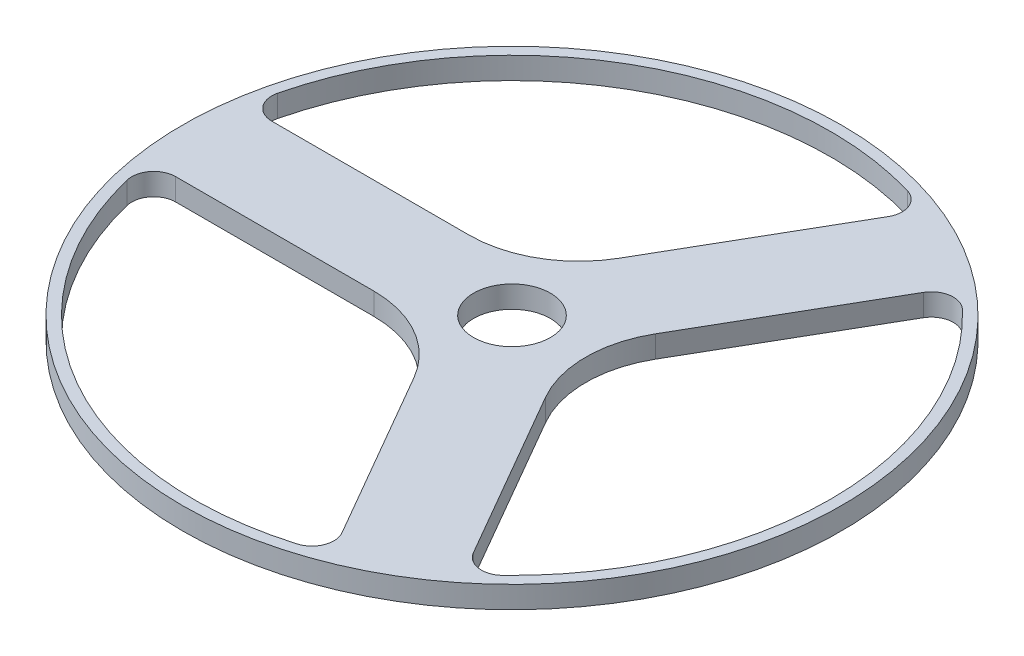
SolidWorks part; units mm, degrees
ref_plane "Front Plane" through (0, 0, 0) normal (0, 0, 1) x (1, 0, 0)
ref_plane "Top Plane" through (0, 0, 0) normal (0, 1, 0) x (1, 0, 0)
ref_plane "Right Plane" through (0, 0, 0) normal (1, 0, 0) x (0, 0, -1)
sketch "Sketch1" plane through (0, 0, 0) normal (0, 1, 0) x (1, 0, 0)
  line L0 (0, 15) -> (0, 0) construction
  line L1 (0, 0) -> (-12.9904, -7.5) construction
  line L2 (0, 0) -> (12.9904, -7.5) construction
  circle A0 centre (0, 0) radius 46.5
  circle A1 centre (0, 15) radius 6.5
  circle A2 centre (-12.9904, -7.5) radius 10
  circle A3 centre (12.9904, -7.5) radius 3.5
  circle A4 centre (0, 0) radius 3.5
  point P3 (0, 15)
  point P8 (12.9904, -7.5)
  point P9 (-12.9904, -7.5)
  point P10 (0, 0)
  dimension "D1" = 93
  dimension "D4" = 13
  dimension "D5" = 20
  dimension "D6" = 7
  dimension "D7" = 7
  dimension "D2" = 15
  dimension "D3" = 3
extrude "Boss-Extrude1" add sketch "Sketch1" along normal blind 2
sketch "Sketch2" plane through (0, 2, 0) normal (0, 1, 0) x (1, 0, 0)
  line L0 (0, 0) -> (12.9904, -7.5) construction
  line L1 (0, 0) -> (0, 46.5) construction
  line L2 (0, 0) -> (-12.9904, -7.5) construction
  line L3 (0, 0) -> (-40.2702, -23.25) construction
  line L4 (0, 0) -> (40.2702, -23.25) construction
  circle A0 centre (0, 0) radius 46.5 construction
  circle A1 centre (-12.9904, -7.5) radius 10 construction
  circle A2 centre (12.9904, -7.5) radius 3.5 construction
  circle A3 centre (0, 0) radius 25
  circle A4 centre (21.6506, -12.5) radius 3
  circle A5 centre (-21.6506, -12.5) radius 3
  circle A6 centre (0, 25) radius 3
  point P22 (0, 0)
  dimension "D1" = 50
  dimension "D2" = 6
  dimension "D3" = 3
ref_plane "Plane1" through (0, 0, 0) normal (-0.5, 0, -0.866) x (-0.866, 0, 0.5)
sketch "Sketch3" plane through (0, 2, 0) normal (0, 1, 0) x (1, 0, 0)
  circle A0 centre (0, 0) radius 3.5
  circle A1 centre (0, 0) radius 5
  dimension "D1" = 10
extrude "Boss-Extrude2" add sketch "Sketch3" along normal blind 100
sketch "Sketch4" plane through (0, 102, 0) normal (0, 1, 0) x (1, 0, 0)
  line L0 (-29, 0) -> (-5.1, 0) construction
  line L6 (0, 0) -> (-1.7447, 3.0342) construction
  line L11 (-8.2882, 4.3733) -> (-28.6683, 4.3733)
  line L16 (-8.2093, -4.3733) -> (-28.6683, -4.3733)
  line L17 (7.9863, 5.0683) -> (18.1286, 22.6353)
  line L18 (0.372, 9.3733) -> (10.5551, 27.0109)
  line L19 (0.4509, -9.3733) -> (10.6194, -26.9857)
  line L20 (7.9863, -4.9317) -> (18.1825, -22.592)
  line L21 (0, 0) -> (-3.028, 1.7553)
  line L22 (0, 0) -> (0.0061, 3.5)
  line L23 (0, 0) -> (3.0342, 1.7447)
  line L24 (0, 0) -> (3.028, -1.7553)
  line L25 (0, 0) -> (-0.0061, -3.5)
  line L26 (0, 0) -> (-3.0342, -1.7447)
  line L27 (0, 0) -> (0, 3.5) construction
  line L28 (-3.5, 0) -> (0, 0) construction
  line L29 (0, 29) -> (0, 54.3686) construction
  circle A0 centre (0, 0) radius 30
  circle A1 centre (0, 0) radius 29
  circle A3 centre (0, 0) radius 3.5
  arc A4 (-8.2093, -4.3733) -> (0.4509, -9.3733) centre (-8.2093, -14.3733) cw
  arc A6 (7.9863, -4.9317) -> (7.9863, 5.0683) centre (16.6465, 0.0683) cw
  arc A7 (-8.2882, 4.3733) -> (0.372, 9.3733) centre (-8.2882, 14.3733) ccw
  point P17 (0, 0)
  point P21 (0.0497, 0.0228)
  point P23 (0, 0)
  point P32 (0, 0)
  point P33 (5.0995, 0.0683)
  dimension "D1" = 60
  dimension "D2" = 58
  dimension "D12" = 10
  dimension "D4" = 3
  dimension "D7" = 8.7466
  dimension "D8" = 30
  dimension "D9" = 30
  dimension "D10" = 3
extrude "Boss-Extrude5" add sketch "Sketch4" along normal blind 2 separate body
fillet "Fillet2" radius 2 6 edges at (18.1825, 103, 22.592) (18.1286, 103, -22.6353) (10.5551, 103, -27.0109) (-28.6683, 103, -4.3733) (-28.6683, 103, 4.3733) (10.6194, 103, 26.9857)
sketch "Sketch5" plane through (0, 102, 0) normal (0, -1, 0) x (1, 0, 0)
  line L0 (0, 0) -> (-30, 0) construction
  line L1 (0, 0) -> (15, 25.9808) construction
  line L2 (0, 0) -> (15, -25.9808) construction
  line L6 (8.384, -16.5215) -> (4.884, -10.4593)
  line L7 (8.384, -16.5215) -> (10.116, -15.5215)
  line L8 (10.116, -15.5215) -> (6.616, -9.4593)
  line L9 (4.884, -10.4593) -> (6.616, -9.4593)
  line L10 (8.384, -16.5215) -> (6.616, -9.4593) construction
  line L11 (10.116, -15.5215) -> (4.884, -10.4593) construction
  circle A0 centre (0, 0) radius 15 construction
  circle A2 centre (-15, 0) radius 1
  circle A3 centre (7.5, 12.9904) radius 3.5
  point P17 (7.5, -12.9904)
  dimension "D1" = 30
  dimension "D2" = 2
  dimension "D3" = 7
  dimension "D4" = 2
  dimension "D5" = 7
extrude "Cut-Extrude1" cut sketch "Sketch5" against normal blind 1
sketch "Sketch6" plane through (0, 0, 0) normal (0, -1, 0) x (1, 0, 0)
  circle A0 centre (0, 0) radius 35
  circle A1 centre (0, 35) radius 2
  circle A2 centre (27.3641, 21.8221) radius 2
  circle A3 centre (34.1225, -7.7882) radius 2
  circle A4 centre (15.1859, -31.5339) radius 2
  circle A5 centre (-15.1859, -31.5339) radius 2
  circle A6 centre (-34.1225, -7.7882) radius 2
  circle A7 centre (-27.3641, 21.8221) radius 2
  point P20 (0, 0)
  dimension "D1" = 70
  dimension "D2" = 4
  dimension "D3" = 7
extrude "Cut-Extrude2" cut sketch "Sketch6" against normal up to next (2 mm away) contours A0 A4 | A0 A4 | A0 A3 | A0 A3 | A0 A2 | A0 A2 | A0 A1 | A0 A1 | A0 A7 | A0 A7 | A0 A6 | A0 A6 | A0 A5 | A0 A5
chamfer "Chamfer2" distance 0.8 angle 45 8 edges at (0, 0, 33) (-27.3641, 0, 19.8221) (-34.1225, 0, -9.7882) (-15.1859, 0, -33.5339) (27.3641, 0, 19.8221) (12.9904, 0, 11) (34.1225, 0, -9.7882) (15.1859, 0, -33.5339)
sketch "Sketch7" plane through (0, 102, 0) normal (0, -1, 0) x (1, 0, 0)
  circle A0 centre (0, 0) radius 61.0857
extrude "Cut-Extrude3" cut sketch "Sketch7" along normal through all
